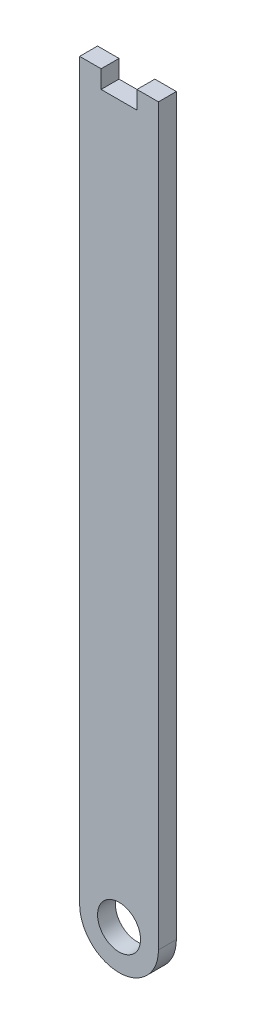
SolidWorks part; units mm, degrees
ref_plane "Front Plane" through (0, 0, 0) normal (1, 0, 0) x (0, 1, 0)
ref_plane "Top Plane" through (0, 0, 0) normal (0, 0, 1) x (0, 1, 0)
ref_plane "Right Plane" through (0, 0, 0) normal (0, 1, 0) x (-1, 0, 0)
sketch "Sketch1" plane through (0, 0, 0) normal (0, 0, 1) x (0, 1, 0)
  line L0 (0, 11) -> (205, 11)
  line L1 (0, -11) -> (205, -11)
  line L14 (205, 11) -> (205, -11) construction
  line L15 (205, 0) -> (200, 0) construction
  line L16 (200, -5) -> (200, 5)
  line L17 (200, 5) -> (205, 5)
  line L18 (200, -5) -> (205, -5)
  line L19 (205, 11) -> (205, 5)
  line L20 (205, -5) -> (205, -11)
  circle A0 centre (0, 0) radius 6
  arc A1 (0, 11) -> (0, -11) centre (0, 0) ccw
  arc A2 (0, -11) -> (0, 11) centre (0, 0) ccw construction
  circle A3 centre (0, 0) radius 11 construction
  point P13 (200, 0)
  dimension "D2" = 12
  dimension "D3" = 205
  dimension "D4" = 10
  dimension "D5" = 5
  dimension "D1" = 5
extrude "Boss-Extrude1" add sketch "Sketch1" along normal mid plane 5
